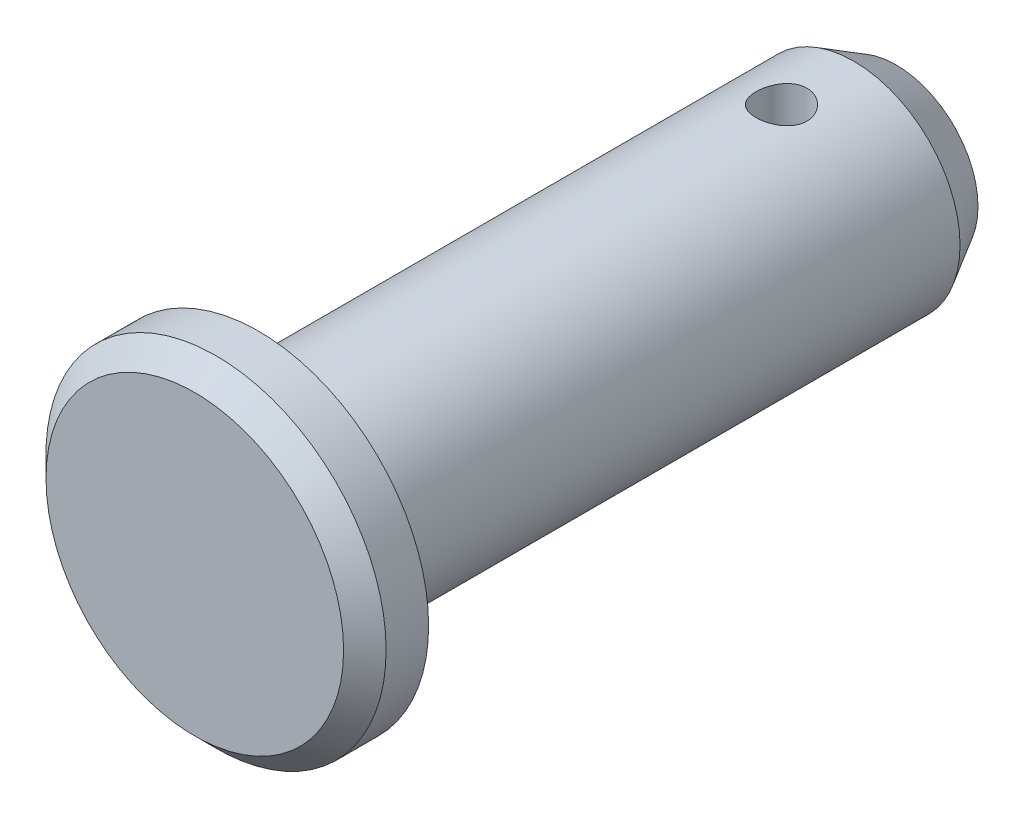
SolidWorks part; units mm, degrees
material "1.0545 (S355N)"
ref_plane "Płaszczyzna przednia" through (0, 0, 0) normal (0, 0, 1) x (1, 0, 0)
ref_plane "Płaszczyzna górna" through (0, 0, 0) normal (0, 1, 0) x (1, 0, 0)
ref_plane "Płaszczyzna prawa" through (0, 0, 0) normal (1, 0, 0) x (0, 0, -1)
sketch "Szkic1" plane through (0, 0, 0) normal (0, 1, 0) x (1, 0, 0)
  line L0 (3.5, -8.25) -> (-3.5, -8.25)
  line L1 (-4, -7.75) -> (-4, -6.75)
  line L2 (-4, -6.75) -> (-2.5, -6.75)
  line L3 (-2.5, -6.75) -> (-2.5, 7.25)
  line L4 (-1.9226, 8.25) -> (1.9226, 8.25)
  line L5 (2.5, 7.25) -> (2.5, -6.75)
  line L6 (2.5, -6.75) -> (4, -6.75)
  line L7 (4, -6.75) -> (4, -7.75)
  line L8 (4, -7.75) -> (3.5, -8.25)
  line L9 (-3.5, -8.25) -> (-4, -7.75)
  line L10 (1.9226, 8.25) -> (2.5, 7.25)
  line L11 (-2.5, 7.25) -> (-1.9226, 8.25)
  line L12 (0, -8.25) -> (0, 8.25)
  point P0 (4, -8.25)
  point P1 (-4, -8.25)
  point P5 (-2.5, 8.25)
  point P6 (2.5, 8.25)
  point P7 (0, 0)
  point P17 (0, 8.25)
  point P19 (0, -8.25)
  dimension "D1" = 8
  dimension "D2" = 5
  dimension "D3" = 1
  dimension "D4" = 30
  dimension "D8" = 30
  dimension "D9" = 15
  dimension "D10" = 1.5
revolve "Obrót1" add sketch "Szkic1" angle 360 about L12
sketch "Szkic2" plane through (0, 0, 0) normal (0, 1, 0) x (1, 0, 0)
  line L0 (2.5, -6.75) -> (-2.5, -6.75) construction
  circle A0 centre (0, 5.55) radius 0.6
  dimension "D2" = 1.2
  dimension "D1" = 12.3
extrude "Wytnij-wyciągnięcie1" cut sketch "Szkic2" against normal through all both and the other way through all contours A0
